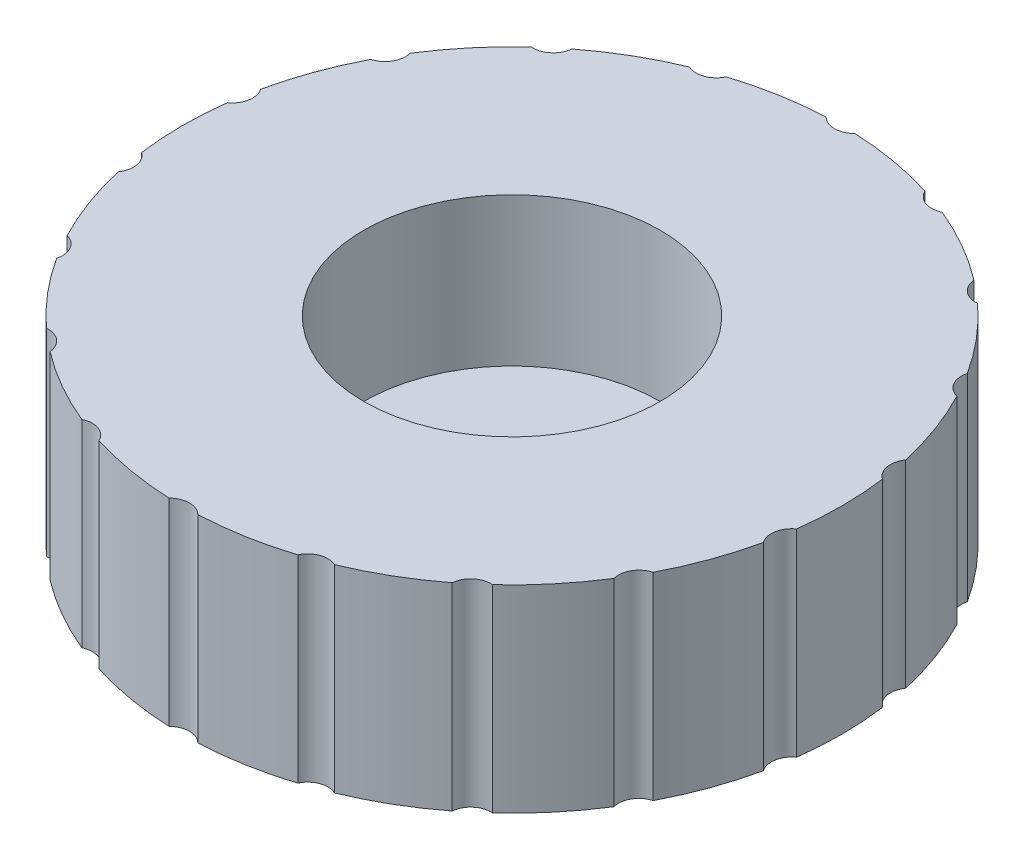
SolidWorks part; units mm, degrees
ref_plane "Front Plane" through (0, 0, 0) normal (0, 0, 1) x (1, 0, 0)
ref_plane "Top Plane" through (0, 0, 0) normal (0, 1, 0) x (1, 0, 0)
ref_plane "Right Plane" through (0, 0, 0) normal (1, 0, 0) x (0, 0, -1)
sketch "Sketch1" plane through (0, 0, 0) normal (0, 1, 0) x (1, 0, 0)
  circle A0 centre (0, 0) radius 45
  circle A1 centre (0, 0) radius 100
  dimension "D1" = 90
  dimension "D2" = 200
extrude "Boss-Extrude1" add sketch "Sketch1" along normal blind 60
sketch "Sketch2" plane through (0, 0, 0) normal (0, -1, 0) x (1, 0, 0)
  circle A0 centre (0, 0) radius 45
extrude "Boss-Extrude2" add sketch "Sketch2" against normal blind 15
sketch "Sketch3" plane through (0, 15, 0) normal (0, 1, 0) x (1, 0, 0)
  line L1 (-6.5, 1.5) -> (-5.2915, 1.5)
  line L2 (-6.5, 1.5) -> (-6.5, -1.5)
  line L3 (-6.5, -1.5) -> (-5.2915, -1.5)
  arc A0 (-5.2915, -1.5) -> (-5.2915, 1.5) centre (0, 0) ccw
  point P2 (-5.5, 0)
  point P22 (0, 0)
  dimension "D1" = 11
  dimension "D2" = 3
sketch "Sketch4" plane through (0, 60, 0) normal (0, 1, 0) x (1, 0, 0)
  arc A0 (-4.5831, 99.8949) -> (4.1279, 99.9148) centre (-0.2375, 104.2603) ccw
  arc A1 (29.8594, 95.438) -> (38.0518, 92.4773) centre (35.436, 98.0539) ccw
  circle A2 centre (0, 0) radius 100 construction
  arc A3 (60.7004, 79.4699) -> (67.3861, 73.8858) centre (66.8353, 80.0207) ccw
  arc A4 (84.22, 53.9165) -> (88.5927, 46.3825) centre (90.1734, 52.3358) ccw
  arc A5 (97.5815, 21.86) -> (99.1136, 13.2848) centre (102.6352, 18.3385) ccw
  arc A6 (99.1731, -12.8331) -> (97.68, -21.4152) centre (102.7176, -17.8707) ccw
  arc A7 (88.8031, -45.9784) -> (84.4648, -53.5323) centre (90.4109, -51.9245) ccw
  arc A8 (67.7221, -73.578) -> (61.0618, -79.1925) centre (67.1992, -79.7154) ccw
  arc A9 (38.4728, -92.303) -> (30.2939, -95.301) centre (35.8823, -97.8914) ccw
  arc A10 (4.5831, -99.8949) -> (-4.1279, -99.9148) centre (0.2375, -104.2603) ccw
  arc A11 (-29.8594, -95.438) -> (-38.0518, -92.4773) centre (-35.436, -98.0539) ccw
  arc A12 (-60.7004, -79.4699) -> (-67.3861, -73.8858) centre (-66.8353, -80.0207) ccw
  arc A13 (-84.22, -53.9165) -> (-88.5927, -46.3825) centre (-90.1734, -52.3358) ccw
  arc A14 (-97.5815, -21.86) -> (-99.1136, -13.2848) centre (-102.6352, -18.3385) ccw
  arc A15 (-99.1731, 12.8331) -> (-97.68, 21.4152) centre (-102.7176, 17.8707) ccw
  arc A16 (-88.8031, 45.9784) -> (-84.4648, 53.5323) centre (-90.4109, 51.9245) ccw
  arc A17 (-67.7221, 73.578) -> (-61.0618, 79.1925) centre (-67.1992, 79.7154) ccw
  arc A18 (-38.4728, 92.303) -> (-30.2939, 95.301) centre (-35.8823, 97.8914) ccw
  arc A19 (-38.4728, 92.303) -> (-30.2939, 95.301) centre (-34.2118, 93.334) cw
  arc A20 (-4.5831, 99.8949) -> (4.1279, 99.9148) centre (-0.2264, 99.4064) cw
  arc A21 (29.8594, 95.438) -> (38.0518, 92.4773) centre (33.7862, 93.4889) cw
  arc A22 (60.7004, 79.4699) -> (67.3861, 73.8858) centre (63.7237, 76.2953) cw
  arc A23 (84.22, 53.9165) -> (88.5927, 46.3825) centre (85.9752, 49.8993) cw
  arc A24 (97.5815, 21.86) -> (99.1136, 13.2848) centre (97.8569, 17.4847) cw
  arc A25 (99.1731, -12.8331) -> (97.68, -21.4152) centre (97.9355, -17.0387) cw
  arc A26 (88.8031, -45.9784) -> (84.4648, -53.5323) centre (86.2017, -49.5071) cw
  arc A27 (67.7221, -73.578) -> (61.0618, -79.1925) centre (64.0707, -76.0042) cw
  arc A28 (38.4728, -92.303) -> (30.2939, -95.301) centre (34.2118, -93.334) cw
  arc A29 (4.5831, -99.8949) -> (-4.1279, -99.9148) centre (0.2264, -99.4064) cw
  arc A30 (-29.8594, -95.438) -> (-38.0518, -92.4773) centre (-33.7862, -93.4889) cw
  arc A31 (-60.7004, -79.4699) -> (-67.3861, -73.8858) centre (-63.7237, -76.2953) cw
  arc A32 (-84.22, -53.9165) -> (-88.5927, -46.3825) centre (-85.9752, -49.8993) cw
  arc A33 (-97.5815, -21.86) -> (-99.1136, -13.2848) centre (-97.8569, -17.4847) cw
  arc A34 (-99.1731, 12.8331) -> (-97.68, 21.4152) centre (-97.9355, 17.0387) cw
  arc A35 (-88.8031, 45.9784) -> (-84.4648, 53.5323) centre (-86.2017, 49.5071) cw
  arc A36 (-67.7221, 73.578) -> (-61.0618, 79.1925) centre (-64.0707, 76.0042) cw
  point P58 (0, 0)
  point P111 (0, 0)
  dimension "D1" = 18
  dimension "D2" = 18
extrude "Cut-Extrude2" cut sketch "Sketch4" against normal blind 85
sketch "Sketch5" plane through (0, 0, 0) normal (0, -1, 0) x (1, 0, 0)
  circle A0 centre (0, 0) radius 70
  dimension "D1" = 140
extrude "Cut-Extrude3" cut sketch "Sketch5" against normal blind 5
extrude "Cut-Extrude4" cut sketch "Sketch3" against normal blind 50
